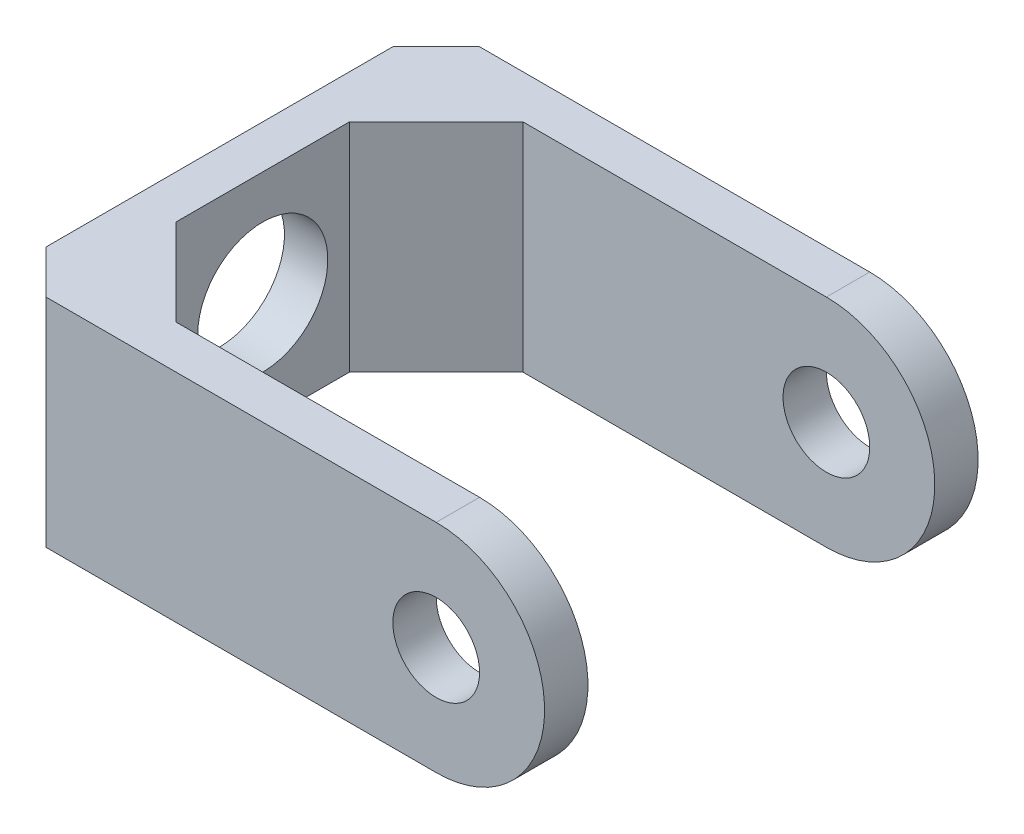
SolidWorks part; units mm, degrees
ref_plane "前视基准面" through (0, 0, 0) normal (0, 0, 1) x (1, 0, 0)
ref_plane "上视基准面" through (0, 0, 0) normal (0, 1, 0) x (1, 0, 0)
ref_plane "右视基准面" through (0, 0, 0) normal (1, 0, 0) x (0, 0, -1)
other "Configuration Table"
sketch "草图1" plane through (0, 0, 0) normal (0, 0, 1) x (1, 0, 0)
  line L1 (0, 0) -> (18, 0)
  line L2 (0, 0) -> (0, 10)
  line L3 (0, 10) -> (18, 10)
  arc A0 (18, 0) -> (18, 10) centre (18, 5) ccw
  circle A1 centre (18, 5) radius 2
  dimension "D3" = 4
  dimension "D1" = 18
  dimension "D2" = 10
extrude "凸台-拉伸1" add sketch "草图1" along normal blind 2
ref_plane "基准面2" through (0, 0, 10) normal (0, 0, 1) x (1, 0, 0)
mirror "镜向1" about plane through (0, 0, 10) normal (0, 0, 1) of bodies 106
sketch "草图6" plane through (0, 0, 0) normal (-1, 0, 0) x (0, 0, 1)
  line L1 (0, 10) -> (20, 10)
  line L2 (0, 10) -> (0, 0)
  line L3 (0, 0) -> (20, 0)
  line L4 (20, 10) -> (20, 0)
extrude "凸台-拉伸5" add sketch "草图6" along normal blind 2
chamfer "倒角2" distance 2 angle 45 2 edges at (-2, 5, 20) (-2, 5, 0)
chamfer "倒角3" distance 4 angle 45 2 edges at (0, 5, 18) (0, 5, 2)
sketch "草图7" plane through (-2, 0, 0) normal (-1, 0, 0) x (0, 0, 1)
  line L0 (2, 10) -> (18, 0) construction
  circle A0 centre (10, 5) radius 3
  dimension "D1" = 6
extrude "切除-拉伸2" cut sketch "草图7" against normal through all
ref_plane "基准面1" through (0, 5, 0) normal (0, 1, 0) x (1, 0, 0)
